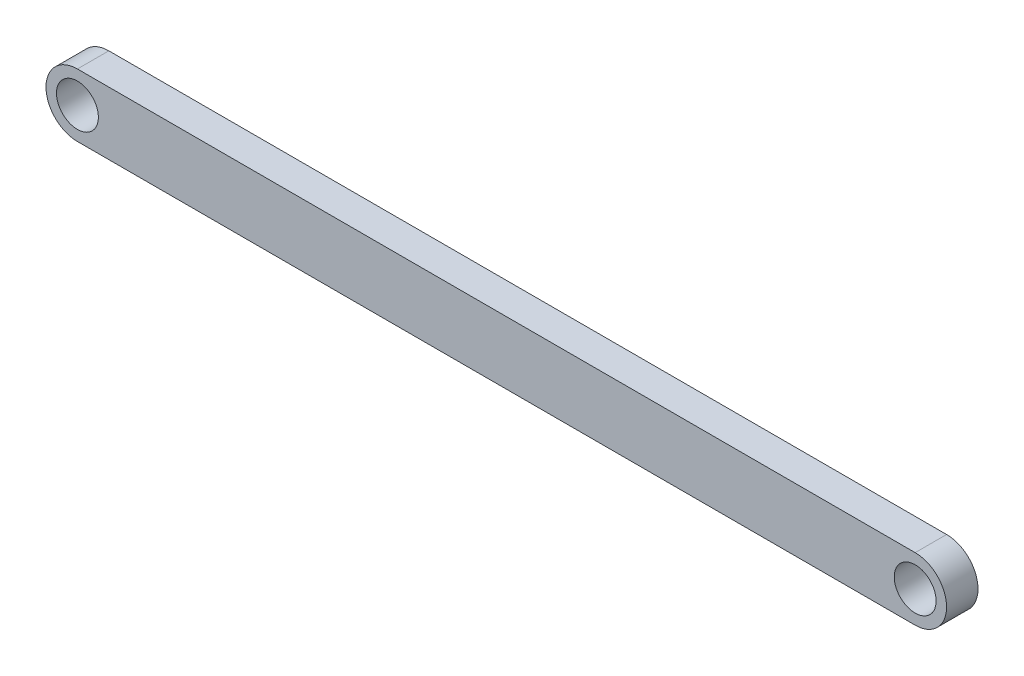
SolidWorks part; units mm, degrees
ref_plane "Front Plane" through (0, 0, 0) normal (0, 0, 1) x (1, 0, 0)
ref_plane "Top Plane" through (0, 0, 0) normal (0, 1, 0) x (1, 0, 0)
ref_plane "Right Plane" through (0, 0, 0) normal (1, 0, 0) x (0, 0, -1)
sketch "Sketch1" plane through (0, 0, 0) normal (0, 0, 1) x (1, 0, 0)
  line L0 (-400, 15) -> (0, 15)
  line L1 (-400, -15) -> (0, -15)
  circle A0 centre (-400, 0) radius 10
  circle A1 centre (0, 0) radius 10
  arc A2 (-400, -15) -> (-400, 15) centre (-400, 0) cw
  arc A3 (0, -15) -> (0, 15) centre (0, 0) ccw
  dimension "D1" = 400
  dimension "D3" = 20
  dimension "D2" = 30
extrude "Extrude1" add sketch "Sketch1" along normal blind 15
